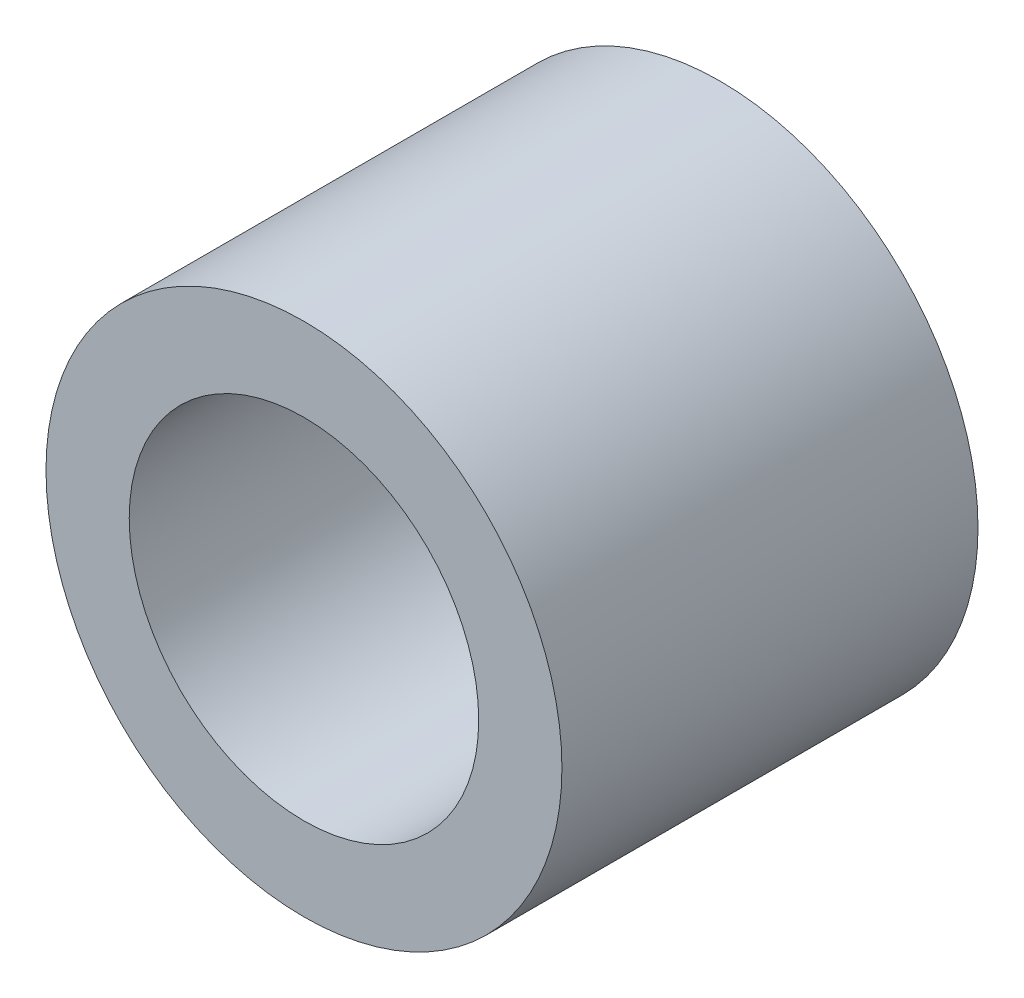
SolidWorks part; units mm, degrees
ref_plane "Front Plane" through (0, 0, 0) normal (0, 0, 1) x (1, 0, 0)
ref_plane "Top Plane" through (0, 0, 0) normal (0, 1, 0) x (1, 0, 0)
ref_plane "Right Plane" through (0, 0, 0) normal (1, 0, 0) x (0, 0, -1)
sketch "Sketch1" plane through (0, 0, 0) normal (0, 0, 1) x (1, 0, 0)
  circle A0 centre (0, 0) radius 2.1
  circle A1 centre (0, 0) radius 3.1
  dimension "D1" = 6.2
  dimension "D2" = 4.2
extrude "Boss-Extrude1" add sketch "Sketch1" along normal mid plane 5
equation "\"ID\"= 4.2"
equation "\"OD\"= 6.2"
equation "\"height\"= 5"
equation "\"D1@Sketch1\"=\"OD\""
equation "\"D2@Sketch1\"=\"ID\""
equation "\"D1@Boss-Extrude1\"=\"height\""
